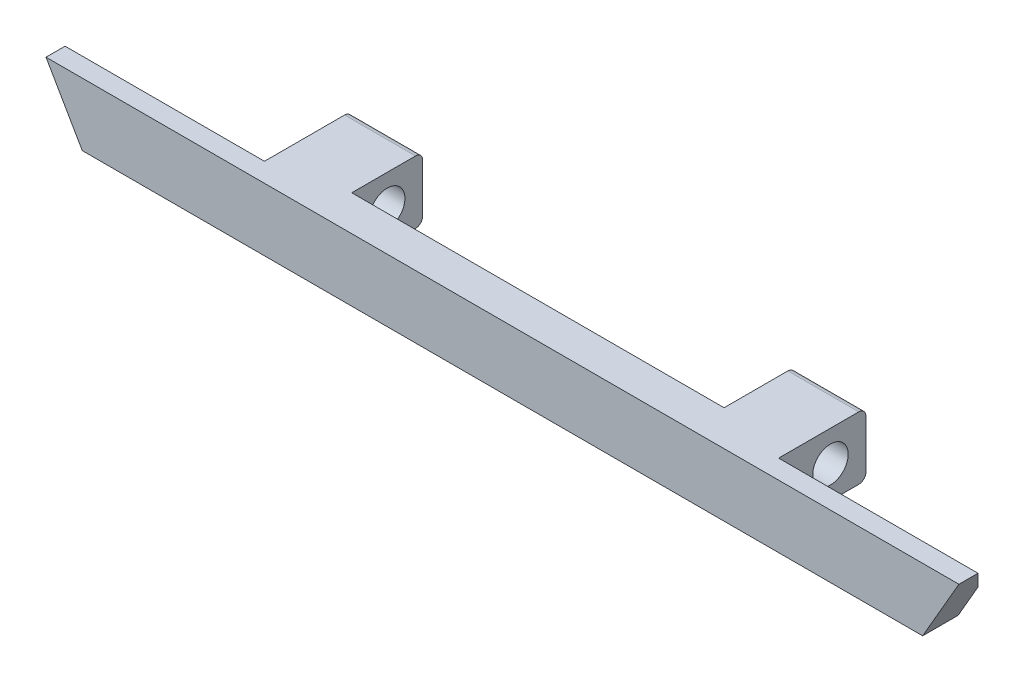
SolidWorks part; units mm, degrees
ref_plane "Front Plane" through (0, 0, 0) normal (0, 0, 1) x (1, 0, 0)
ref_plane "Top Plane" through (0, 0, 0) normal (0, 1, 0) x (1, 0, 0)
ref_plane "Right Plane" through (0, 0, 0) normal (1, 0, 0) x (0, 0, -1)
sketch "Sketch1" plane through (0, 0, 0) normal (0, 0, 1) x (1, 0, 0)
  line L0 (0, 0) -> (592.5, 0)
  line L1 (592.5, 0) -> (643.63, 88.5598)
  line L2 (643.63, 88.5598) -> (-643.63, 88.5598)
  line L3 (-643.63, 88.5598) -> (-592.5, 0)
  line L4 (-592.5, 0) -> (0, 0)
  dimension "D1" = 60
  dimension "D2" = 1287.26
  dimension "D3" = 1185
extrude "Boss-Extrude1" add sketch "Sketch1" along normal blind 50
sketch "Sketch2" plane through (0, 0, 0) normal (0, 0, -1) x (-1, 0, 0)
  line L0 (0, 0) -> (-312.5, 0)
  line L1 (592.5, 0) -> (-592.5, 0) construction
  line L2 (-312.5, 0) -> (-312.5, 44.2799)
  line L3 (0, 0) -> (312.5, 0)
  line L4 (312.5, 0) -> (312.5, 44.2799)
  line L5 (-312.5, 44.2799) -> (-312.5, 88.5598) construction
  line L6 (-362.5, 88.5598) -> (-262.5, 88.5598)
  line L7 (-362.5, 88.5598) -> (-362.5, 0)
  line L8 (-362.5, 0) -> (-262.5, 0)
  line L9 (-262.5, 88.5598) -> (-262.5, 0)
  line L10 (-362.5, 88.5598) -> (-262.5, 0) construction
  line L11 (-362.5, 0) -> (-262.5, 88.5598) construction
  line L12 (262.5, 88.5598) -> (362.5, 88.5598)
  line L13 (262.5, 88.5598) -> (262.5, 0)
  line L14 (262.5, 0) -> (362.5, 0)
  line L15 (362.5, 88.5598) -> (362.5, 0)
  line L16 (262.5, 88.5598) -> (362.5, 0) construction
  line L17 (262.5, 0) -> (362.5, 88.5598) construction
  line L18 (-643.63, 88.5598) -> (643.63, 88.5598) construction
  line L19 (312.5, 44.2799) -> (312.5, 88.5598) construction
  dimension "D1" = 312.5
  dimension "D2" = 100
extrude "Boss-Extrude2" add sketch "Sketch2" along normal blind 100
sketch "Sketch3" plane through (362.5, 0, 0) normal (1, 0, 0) x (0, 0, -1)
  line L0 (50, 0) -> (50, 44.2799) construction
  line L1 (100, 0) -> (0, 0) construction
  line L2 (50, 44.2799) -> (100, 44.2799) construction
  line L3 (100, 88.5598) -> (100, 0) construction
  circle A0 centre (50, 44.2799) radius 25
  dimension "D1" = 50
extrude "Cut-Extrude1" cut sketch "Sketch3" against normal through all
fillet "Fillet1" radius 10 4 edges at (312.5, 0, -100) (312.5, 88.5598, -100) (-312.5, 88.5598, -100) (-312.5, 0, -100)
chamfer "Chamfer1" distance 40 angle 30 2 edges at (-503.065, 88.5598, 0) (503.065, 88.5598, 0)
